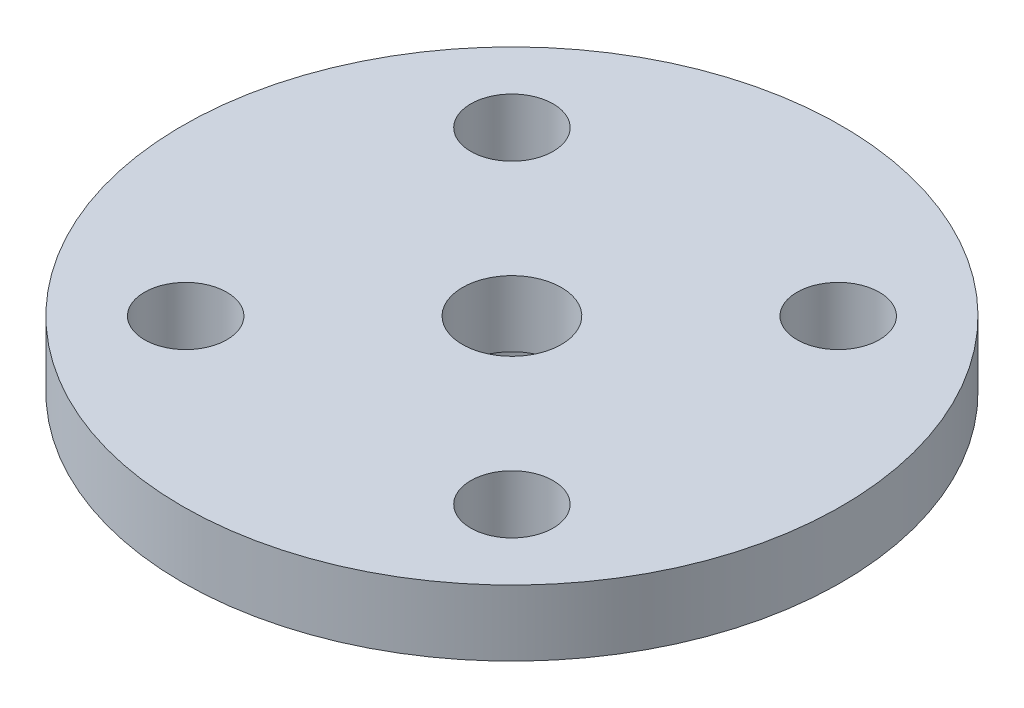
SolidWorks part; units mm, degrees
material "1060 Alloy"
ref_plane "Front Plane" through (0, 0, 0) normal (0, 0, 1) x (1, 0, 0)
ref_plane "Top Plane" through (0, 0, 0) normal (0, 1, 0) x (1, 0, 0)
ref_plane "Right Plane" through (0, 0, 0) normal (1, 0, 0) x (0, 0, -1)
sketch "Sketch1" plane through (0, 0, 0) normal (1, 0, 0) x (0, 0, -1)
  line L0 (0, 0) -> (-10, 0)
  line L1 (-10, 0) -> (-10, -2)
  line L2 (-10, -2) -> (-4.5, -2)
  line L3 (-4.5, -2) -> (-4.5, -5)
  line L4 (-4.5, -5) -> (0, -5)
  line L5 (0, 0) -> (0, -5)
  dimension "D1" = 2
  dimension "D2" = 5
  dimension "D3" = 10
  dimension "D4" = 4.5
revolve "Revolve1" add sketch "Sketch1" angle 360 about L5
hole_wizard "Tap Drill for M3x0.5 Tap1" positions "Sketch3" profile "Sketch4" hole size "M3x0.5" standard "ANSI Metric" end condition through all
sketch "Sketch3" plane through (0, -2, 0) normal (0, -1, 0) x (-1, 0, 0)
  line L1 (-4.9497, -4.9497) -> (4.9497, -4.9497) construction
  line L2 (-4.9497, -4.9497) -> (-4.9497, 4.9497) construction
  line L3 (-4.9497, 4.9497) -> (4.9497, 4.9497) construction
  line L4 (4.9497, -4.9497) -> (4.9497, 4.9497) construction
  line L5 (-4.9497, -4.9497) -> (4.9497, 4.9497) construction
  line L6 (-4.9497, 4.9497) -> (4.9497, -4.9497) construction
  point P2 (4.9497, 4.9497)
  point P107 (-4.9497, -4.9497)
  point P108 (-4.9497, 4.9497)
  point P109 (4.9497, -4.9497)
  dimension "D1" = 14
sketch "Sketch4" plane through (-4.9497, -2, -4.9497) normal (1, 0, 0) x (0, 0, -1)
  line L0 (0, 0) -> (0, 2)
  line L1 (0, 2) -> (1.25, 2)
  line L2 (1.25, 2) -> (1.25, 0.025)
  line L3 (1.25, 0.025) -> (1.275, 0)
  line L5 (1.275, 0) -> (0, 0)
  line L6 (-1.25, 0.025) -> (-1.275, 0) construction
  line L11 (0, -6.35) -> (0, 107.95) construction
  dimension "Thru Hole Dia." = 2.5
  dimension "Thru Hole Depth" = 2
  dimension "Near C'Sink Dia." = 2.55
  dimension "Near C'Sink Angle" = 90
cosmetic thread "Cosmetic Thread1" parameters "D2"=3.5
cosmetic thread "Cosmetic Thread2" parameters "D2"=3.5
cosmetic thread "Cosmetic Thread3" parameters "D2"=3.5
cosmetic thread "Cosmetic Thread4" parameters "D2"=3.5
sketch "Sketch5" plane through (0, -5, 0) normal (0, -1, 0) x (-1, 0, 0)
  circle A0 centre (0, 0) radius 2.75
  dimension "D1" = 5.5
extrude "Cut-Extrude1" cut sketch "Sketch5" against normal up to surface (3 mm away) up to face at (-4.9497, -2, -6.2247)
sketch "Sketch6" plane through (0, -2, 0) normal (0, -1, 0) x (-1, 0, 0)
  circle A0 centre (0, 0) radius 1.5
  dimension "D1" = 3
extrude "Cut-Extrude2" cut sketch "Sketch6" against normal through all
